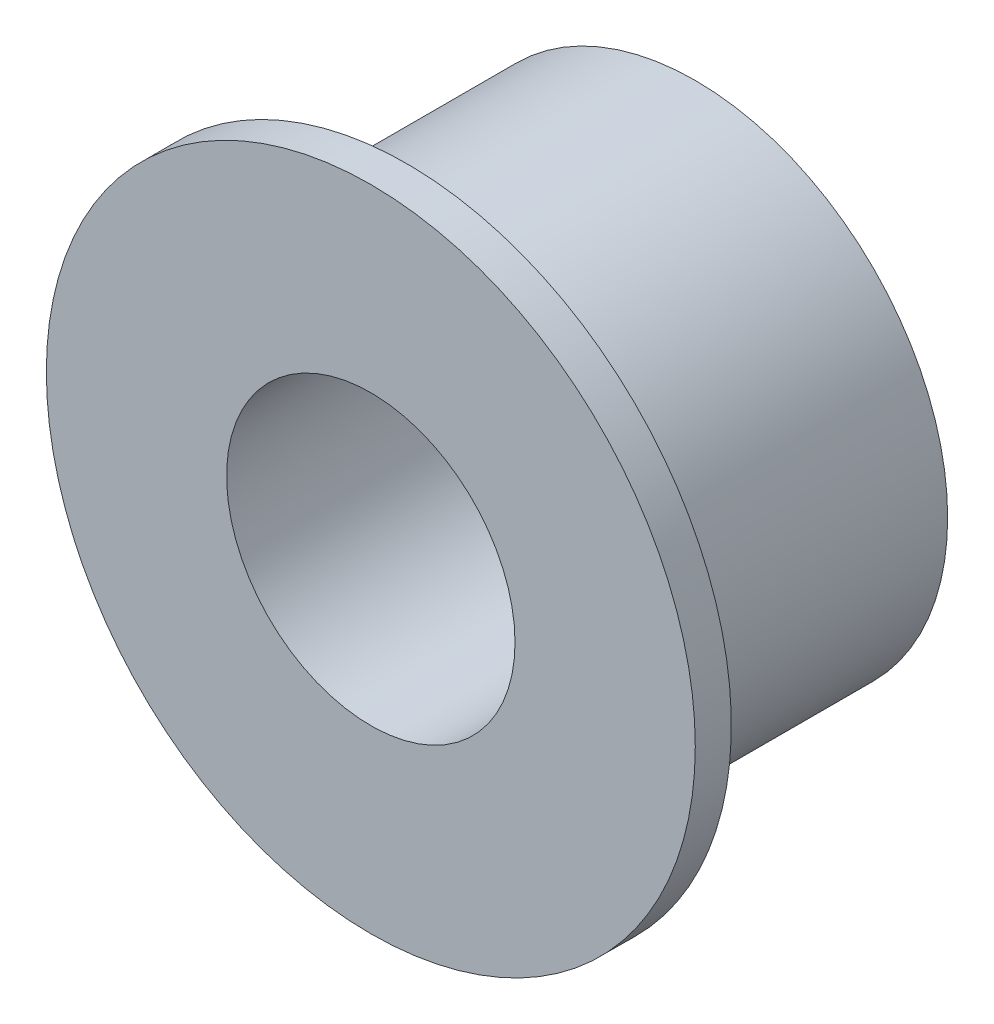
SolidWorks part; units mm, degrees
ref_plane "Front Plane" through (0, 0, 0) normal (0, 0, 1) x (1, 0, 0)
ref_plane "Top Plane" through (0, 0, 0) normal (0, 1, 0) x (1, 0, 0)
ref_plane "Right Plane" through (0, 0, 0) normal (1, 0, 0) x (0, 0, -1)
sketch "Sketch2" plane through (0, 0, 0) normal (0, 0, 1) x (1, 0, 0)
  circle A0 centre (0, 0) radius 9
extrude "Boss-Extrude1" add sketch "Sketch2" along normal blind 9
sketch "Sketch3" plane through (0, 0, 9) normal (0, 0, 1) x (1, 0, 0)
  circle A0 centre (0, 0) radius 4
extrude "Cut-Extrude1" cut sketch "Sketch3" against normal blind 7
sketch "Sketch4" plane through (0, 0, 0) normal (0, 0, -1) x (-1, 0, 0)
  circle A0 centre (0, 0) radius 7
  circle A1 centre (0, 0) radius 9
extrude "Cut-Extrude2" cut sketch "Sketch4" against normal blind 8
